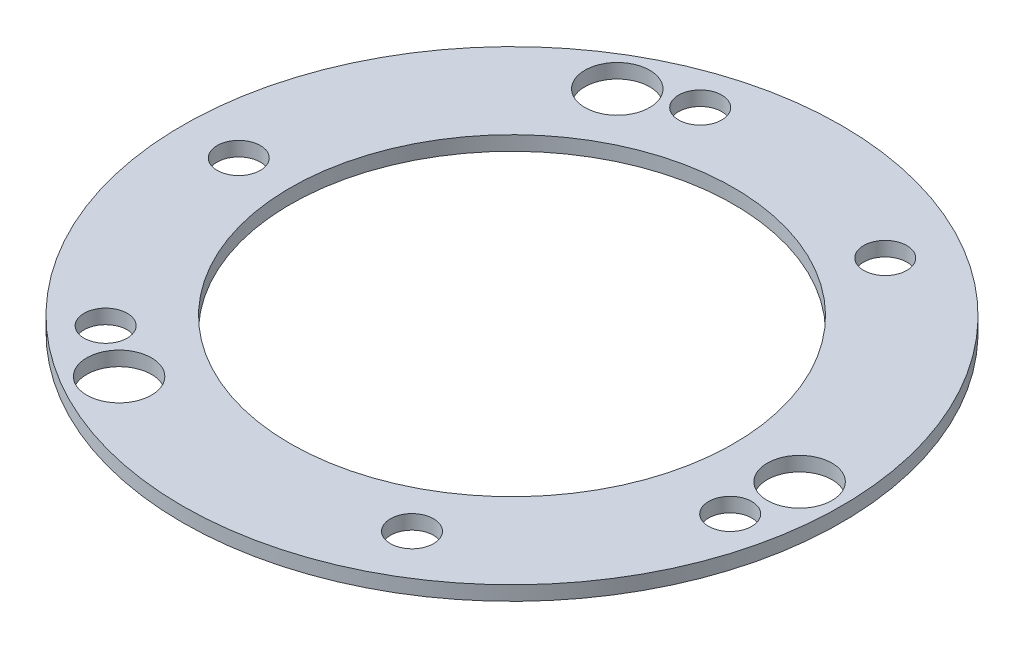
SolidWorks part; units mm, degrees
ref_plane "前视基准面" through (0, 0, 0) normal (0, 0, 1) x (1, 0, 0)
ref_plane "上视基准面" through (0, 0, 0) normal (0, 1, 0) x (1, 0, 0)
ref_plane "右视基准面" through (0, 0, 0) normal (1, 0, 0) x (0, 0, -1)
sketch "草图1" plane through (0, 0, 0) normal (0, 1, 0) x (1, 0, 0)
  line L0 (-267, 0) -> (265, 0) construction
  line L1 (133.5, 231.2288) -> (-133.5, -231.2288) construction
  line L2 (-133.5, 231.2288) -> (133.5, -231.2288) construction
  circle A0 centre (0, 0) radius 240
  circle A1 centre (120, 207.8461) radius 27
  circle A2 centre (-120, 207.8461) radius 27
  circle A4 centre (120, -207.8461) radius 27
  circle A5 centre (-120, -207.8461) radius 27
  circle A6 centre (-240, 0) radius 27
  circle A7 centre (240, 0) radius 27
  circle A8 centre (0, 0) radius 275
  circle A9 centre (0, 0) radius 205
  circle A10 centre (234.2578, -52.185) radius 18
  point P9 (120, 207.8461)
  point P10 (240, 0)
  point P11 (-120, 207.8461)
  point P12 (-240, 0)
  point P13 (-120, -207.8461)
  point P14 (120, -207.8461)
  dimension "D1" = 480
  dimension "D4" = 54
  dimension "D5" = 54
  dimension "D6" = 550
  dimension "D7" = 54
  dimension "D8" = 54
  dimension "D9" = 54
  dimension "D10" = 54
  dimension "D11" = 410
  dimension "D12" = 52.5
  dimension "D13" = 36
  dimension "D2" = 60
  dimension "D3" = 60
sketch "草图3" plane through (0, 0, 0) normal (0, 1, 0) x (1, 0, 0)
  circle A0 centre (0, 0) radius 185
  circle A1 centre (0, 0) radius 275
  circle A2 centre (240, 0) radius 27
  circle A3 centre (234.2578, -52.185) radius 18
  circle A8 centre (-120, -207.8461) radius 27
  circle A9 centre (-120, 207.8461) radius 27
  circle A10 centre (-71.9353, 228.9657) radius 18
  circle A11 centre (0, 0) radius 240 construction
  circle A12 centre (-162.3225, -176.7807) radius 18
  dimension "D1" = 550
  dimension "D2" = 370
  dimension "D3" = 54
  dimension "D4" = 36
  dimension "D6" = 54
  dimension "D5" = 36
  dimension "D7" = 52.5
  dimension "D8" = 54
  dimension "D9" = 36
  dimension "D10" = 52.5
extrude "凸台-拉伸1" add sketch "草图3" along normal blind 12
sketch "草图4" plane through (0, 0, 0) normal (0, 1, 0) x (1, 0, 0)
  line L2 (-267, 0) -> (265, 0) construction
  line L3 (133.5, 231.2288) -> (-133.5, -231.2288) construction
  line L4 (-133.5, 231.2288) -> (133.5, -231.2288) construction
  circle A0 centre (-228, 0) radius 18
  circle A4 centre (114, 197.4538) radius 18
  circle A5 centre (114, -197.4538) radius 18
  dimension "D1" = 36
  dimension "D2" = 228
  dimension "D3" = 36
  dimension "D4" = 36
  dimension "D5" = 228
  dimension "D6" = 228
extrude "切除-拉伸2" cut sketch "草图4" along normal blind 12 and the other way through all
